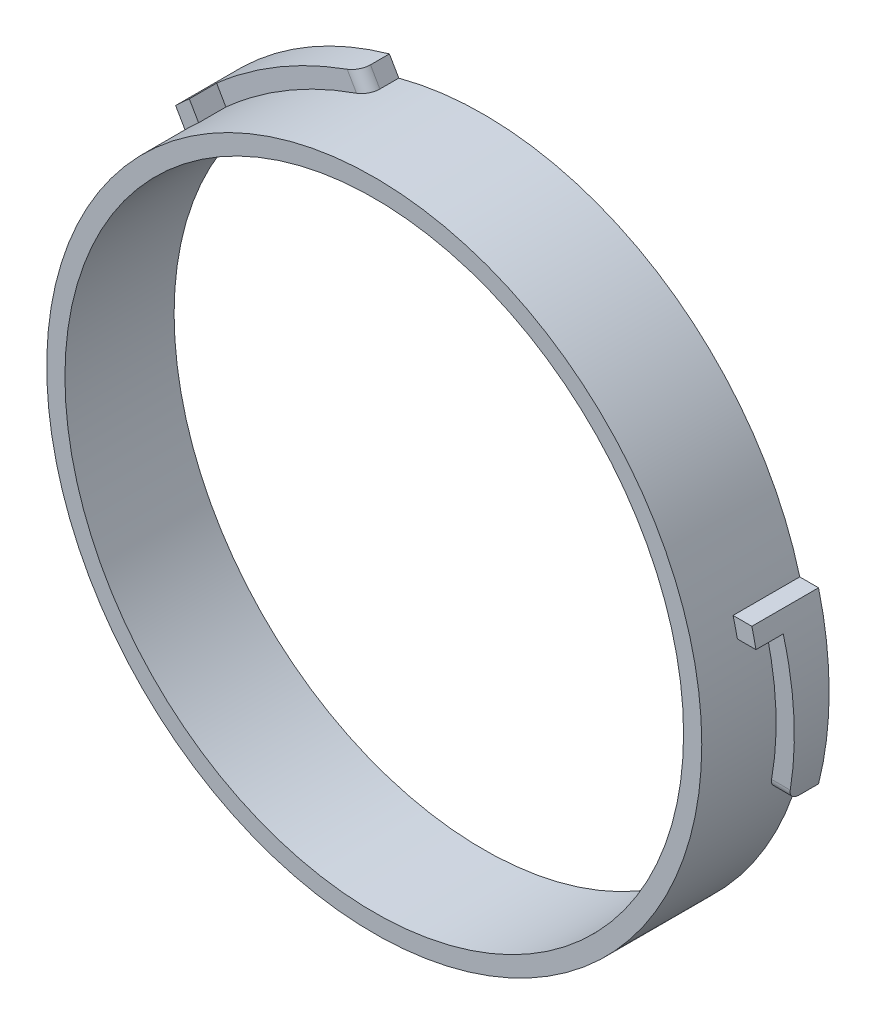
SolidWorks part; units mm, degrees
ref_plane "Спереди" through (0, 0, 0) normal (0, 0, 1) x (1, 0, 0)
ref_plane "Сверху" through (0, 0, 0) normal (0, 1, 0) x (1, 0, 0)
ref_plane "Справа" through (0, 0, 0) normal (1, 0, 0) x (0, 0, -1)
other "Configuration Table"
sketch "Эскиз1" plane through (0, 0, 0) normal (0, 1, 0) x (1, 0, 0)
  line L6 (0, 0) -> (-54, 0)
  line L7 (-54, 0) -> (-54, 145)
  line L8 (-54, 145) -> (-51, 145)
  line L9 (-51, 145) -> (-51, 3)
  line L10 (-51, 3) -> (0, 3)
  line L11 (0, 3) -> (0, 0)
  dimension "D1" = 3
  dimension "D2" = 3
  dimension "D3" = 145
  dimension "D4" = 54
revolve "Повернуть1" add sketch "Эскиз1" angle 360 about L11
ref_plane "Плоскость2" through (57, 0, 0) normal (1, 0, 0) x (0, 0, -1)
sketch "Эскиз2" plane through (57, 0, 0) normal (1, 0, 0) x (0, 0, -1)
  line L0 (145, 14) -> (145, -14)
  line L1 (145, -54) -> (145, 54) construction
  line L2 (145, -14) -> (140, -14)
  line L3 (140, -14) -> (138.5, 11)
  line L4 (138.5, 11) -> (134, 11)
  line L5 (134, 11) -> (134, 14)
  line L6 (134, 14) -> (145, 14)
  point P8 (0, 0)
  dimension "D1" = 28
  dimension "D2" = 3
  dimension "D3" = 6.5
  dimension "D4" = 11
  dimension "D5" = 5
  dimension "D6" = 14
extrude "Бобышка-Вытянуть1" add sketch "Эскиз2" against normal blind 10
fillet "Скругление1" radius 2 1 edges at (54.5768, -14, -140)
pattern_circular "Круговой массив2" count 3 over 360 about axis through (0, 0, 0) along (0, 0, 1) of "Бобышка-Вытянуть1", "Скругление1"
sketch "Эскиз3" plane through (0, 0, -145) normal (0, 0, -1) x (-1, 0, 0)
  circle A0 centre (0, 0) radius 51
extrude "Вырез-Вытянуть1" cut sketch "Эскиз3" against normal blind 15
sketch "Эскиз4" plane through (0, 0, -145) normal (0, 0, -1) x (-1, 0, 0)
  circle A0 centre (0, 0) radius 57
  circle A1 centre (0, 0) radius 62.6187
extrude "Вырез-Вытянуть2" cut sketch "Эскиз4" against normal blind 15
chamfer "Фаска1" distance 2 angle 45 1 edges at (-54, 0, 0)
sketch "Эскиз5" plane through (0, 0, 0) normal (0, 0, 1) x (1, 0, 0)
  circle A0 centre (0, 0) radius 42.5
  dimension "D1" = 85
fillet "Скругление2" radius 5 1 edges at (-51, 0, -3)
extrude "Бобышка-Вытянуть2" add sketch "Эскиз5" along normal blind 3
sketch "Эскиз7" plane through (0, 0, 3) normal (0, 0, 1) x (1, 0, 0)
  circle A0 centre (0, 0) radius 39.5
  dimension "D1" = 79
extrude "Вырез-Вытянуть3" cut sketch "Эскиз7" against normal up to surface (3 mm away) up to face at (42.5, 0, 0)
sketch "Эскиз8" plane through (0, 0, 0) normal (0, 0, 1) x (1, 0, 0)
  line L0 (-1.5, -41) -> (-1.5, 41)
  line L1 (-1.5, -41) -> (1.5, -41)
  line L2 (-1.5, 41) -> (1.5, 41)
  line L3 (1.5, -41) -> (1.5, 41)
  line L4 (-1.5, -41) -> (1.5, 41) construction
  line L5 (-1.5, 41) -> (1.5, -41) construction
  line L6 (-41, -1.5) -> (41, -1.5)
  line L7 (-41, -1.5) -> (-41, 1.5)
  line L8 (41, -1.5) -> (41, 1.5)
  line L9 (-41, 1.5) -> (41, 1.5)
  line L10 (-41, -1.5) -> (41, 1.5) construction
  line L11 (41, -1.5) -> (-41, 1.5) construction
  circle A0 centre (0, 0) radius 8
  circle M1 centre (0, 0) radius 39.5
  dimension "D1" = 16
  dimension "D2" = 3
  dimension "D3" = 82
  dimension "D4" = 82
  dimension "D5" = 3
extrude "Бобышка-Вытянуть4" add sketch "Эскиз8" along normal blind 3 contours A0 L3 L0 M1 | L3 A0 L0 L9 | L9 A0 L3 | L6 A0 L9 L3 | A0 L6 L9 M1 | L3 A0 L6 | L0 A0 L3 L6 | L9 L0 L6 L3 | L0 A0 L9 | L9 A0 L6 L0 | A0 L9 L6 M1 | L6 A0 L0 | A0 L0 L3 M1
sketch "Эскиз11" plane through (0, 0, 3) normal (0, 0, 1) x (1, 0, 0)
  circle A0 centre (0, 0) radius 73.4827
extrude "Вырез-Вытянуть4" cut sketch "Эскиз11" against normal blind 130
equation "\"d\"=3"
equation "\"D1@Эскиз1\"=\"d\""
equation "\"D2@Эскиз1\"=\"d\""
